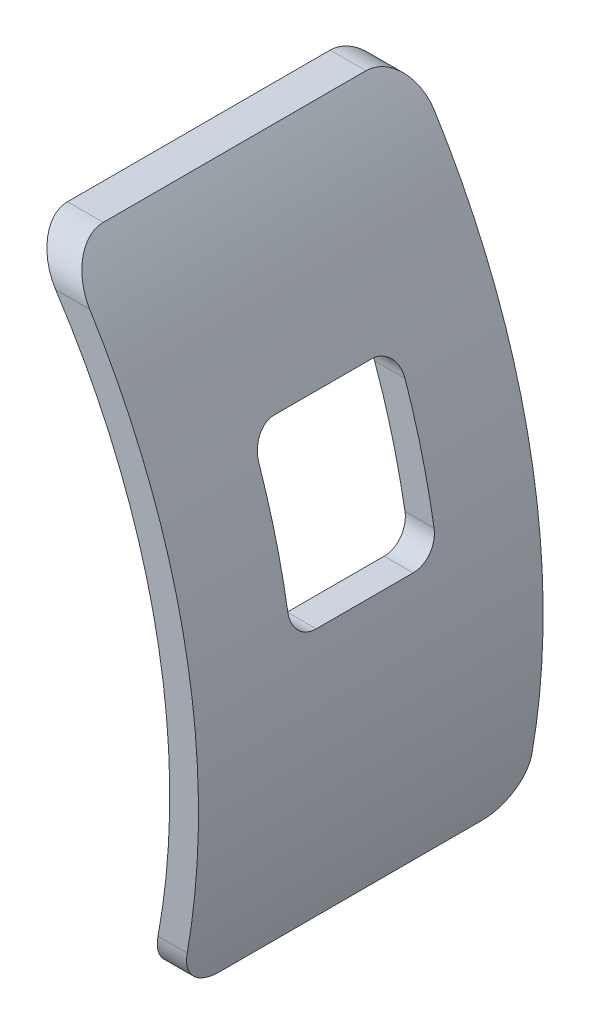
SolidWorks part; units mm, degrees
ref_plane "Front Plane" through (0, 0, 0) normal (0, 0, 1) x (1, 0, 0)
ref_plane "Top Plane" through (0, 0, 0) normal (0, 1, 0) x (1, 0, 0)
ref_plane "Right Plane" through (0, 0, 0) normal (1, 0, 0) x (0, 0, -1)
sketch "Sketch1" plane through (0, 0, 0) normal (0, 0, 1) x (1, 0, 0)
  line L0 (-2063.2072, -609.6) -> (2063.2072, -609.6) construction
  line L1 (-2087.4164, -520.7) -> (2087.4164, -520.7) construction
  line L2 (1818.7163, 1308.1) -> (1818.7163, -520.7) construction
  line L3 (1818.7163, -520.7) -> (2178.9277, -520.7) construction
  line L4 (1708.0136, 1308.1) -> (1818.7163, 1308.1)
  line L5 (2087.4164, -520.7) -> (2178.9277, -520.7)
  line L6 (1708.0136, 1308.1) -> (1708.0136, -520.7) construction
  circle A0 centre (0, 0) radius 2240.28 construction
  circle A1 centre (0, 0) radius 2151.38 construction
  arc A2 (2178.9277, -520.7) -> (1818.7163, 1308.1) centre (0, 0) ccw
  arc A3 (2087.4164, -520.7) -> (1708.0136, 1308.1) centre (0, 0) ccw
  point P6 (0, -2151.38)
  dimension "D1" = 4480.56
  dimension "D2" = 88.9
  dimension "D5" = 1828.8
  dimension "D7" = 1828.8
  dimension "D3" = 1541.78
  dimension "D4" = 88.9
  dimension "D6" = 0
extrude "Boss-Extrude2" add sketch "Sketch1" along normal blind 1066.8
sketch "Sketch2" plane through (0, 0, 0) normal (1, 0, 0) x (0, 0, -1)
  line L0 (-1066.8, 1308.1) -> (0, 1308.1) construction
  line L1 (-683.4606, 291.5082) -> (-383.3394, 291.5082)
  line L2 (-759.6606, 367.7082) -> (-759.6606, 724.4918)
  line L3 (-683.4606, 800.6918) -> (-383.3394, 800.6918)
  line L4 (-307.1394, 367.7082) -> (-307.1394, 724.4918)
  line L5 (-759.6606, 291.5082) -> (-307.1394, 800.6918) construction
  line L6 (-759.6606, 800.6918) -> (-307.1394, 291.5082) construction
  arc A0 (-683.4606, 800.6918) -> (-759.6606, 724.4918) centre (-683.4606, 724.4918) ccw
  arc A1 (-759.6606, 367.7082) -> (-683.4606, 291.5082) centre (-683.4606, 367.7082) ccw
  arc A2 (-307.1394, 367.7082) -> (-383.3394, 291.5082) centre (-383.3394, 367.7082) cw
  arc A3 (-307.1394, 724.4918) -> (-383.3394, 800.6918) centre (-383.3394, 724.4918) ccw
  point P0 (-533.4, 546.1)
  point P8 (-533.4, 1308.1)
  dimension "D2" = 76.2
  dimension "D1" = 762
extrude "Cut-Extrude1" cut sketch "Sketch2" against normal through all both and the other way through all
fillet "Fillet1" radius 127 4 edges at (2133.1721, -520.7, 0) (2133.1721, -520.7, 1066.8) (1763.3649, 1308.1, 0) (1763.3649, 1308.1, 1066.8)
